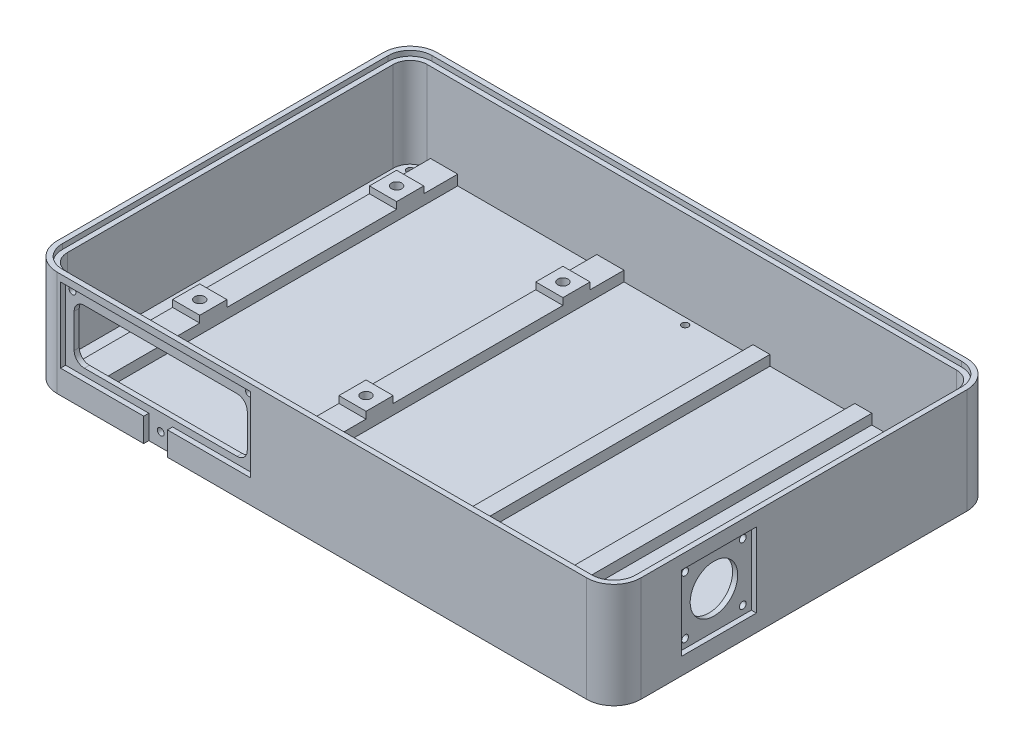
SolidWorks part; units mm, degrees
ref_plane "Спереди" through (0, 0, 0) normal (0, 0, 1) x (1, 0, 0)
ref_plane "Сверху" through (0, 0, 0) normal (0, 1, 0) x (1, 0, 0)
ref_plane "Справа" through (0, 0, 0) normal (1, 0, 0) x (0, 0, -1)
sketch "Эскиз1" plane through (0, 0, 0) normal (0, 1, 0) x (1, 0, 0)
  line L1 (8, 0) -> (164, 0)
  line L2 (0, 8) -> (0, 104)
  line L3 (8, 112) -> (164, 112)
  line L4 (172, 8) -> (172, 104)
  line L5 (8, 109) -> (164, 109)
  line L6 (3, 104) -> (3, 8)
  line L7 (8, 3) -> (164, 3)
  line L8 (169, 104) -> (169, 8)
  arc A0 (164, 0) -> (172, 8) centre (164, 8) ccw
  arc A2 (164, 109) -> (169, 104) centre (164, 104) cw
  arc A3 (172, 104) -> (164, 112) centre (164, 104) ccw
  arc A4 (8, 0) -> (0, 8) centre (8, 8) cw
  arc A5 (3, 8) -> (8, 3) centre (8, 8) ccw
  arc A6 (8, 109) -> (3, 104) centre (8, 104) ccw
  arc A7 (8, 112) -> (0, 104) centre (8, 104) ccw
  arc A8 (164, 3) -> (169, 8) centre (164, 8) ccw
  point P15 (169, 109)
  point P18 (172, 112)
  point P21 (0, 0)
  point P24 (3, 3)
  point P27 (3, 109)
  point P30 (0, 112)
  dimension "D7" = 8
  dimension "D8" = 5
  dimension "D9" = 5
  dimension "D10" = 5
  dimension "D11" = 5
  dimension "D1" = 172
  dimension "D2" = 112
  dimension "D3" = 166
  dimension "D4" = 106
  dimension "D5" = 3
  dimension "D6" = 3
extrude "Бобышка-Вытянуть1" add sketch "Эскиз1" along normal blind 28
sketch "Эскиз3" plane through (0, 0, 0) normal (0, 1, 0) x (1, 0, 0)
  line L0 (164, 109) -> (8, 109) construction
  line L1 (9, 109) -> (17, 109)
  line L2 (9, 109) -> (9, 3)
  line L3 (9, 3) -> (17, 3)
  line L4 (17, 109) -> (17, 3)
  line L6 (8, 3) -> (164, 3) construction
  line L9 (0, 104) -> (0, 8) construction
  line L12 (58, 109) -> (66, 109)
  line L13 (58, 109) -> (58, 3)
  line L14 (58, 3) -> (66, 3)
  line L15 (66, 109) -> (66, 3)
  dimension "D1" = 0
  dimension "D2" = 0
  dimension "D3" = 0
  dimension "D4" = 0
  dimension "D5" = 49
  dimension "D6" = 49
  dimension "D7" = 9
extrude "Бобышка-Вытянуть2" add sketch "Эскиз3" along normal blind 3 separate body
sketch "Эскиз6" plane through (0, 0, 0) normal (0, 1, 0) x (1, 0, 0)
  line L0 (0, 8) -> (0, 104)
  line L1 (8, 112) -> (164, 112)
  line L2 (164, 0) -> (8, 0)
  line L3 (172, 8) -> (172, 104)
  arc A0 (172, 8) -> (164, 0) centre (164, 8) cw
  arc A1 (172, 104) -> (164, 112) centre (164, 104) ccw
  arc A2 (8, 112) -> (0, 104) centre (8, 104) ccw
  arc A3 (0, 8) -> (8, 0) centre (8, 8) ccw
  point P13 (0, 0)
  dimension "D1" = 8
  dimension "D2" = 112
  dimension "D3" = 172
extrude "Бобышка-Вытянуть3" add sketch "Эскиз6" against normal blind 3
hole_wizard "Цековка для  болта с шестигранной головкой M51" positions "Эскиз15" profile "Эскиз14" counterbore size "M5" standard "Ansi Metric" end condition up to next
sketch "Эскиз15" plane through (0, -3, 0) normal (0, -1, 0) x (-1, 0, 0)
  line L0 (-164, 112) -> (-8, 112) construction
  line L1 (-172, 8) -> (-172, 104) construction
  line L2 (-8, 0) -> (-164, 0) construction
  line L3 (0, 104) -> (0, 8) construction
  line L4 (-164, 112) -> (-8, 112) construction
  line L5 (0, 104) -> (0, 8) construction
  line L6 (-8, 0) -> (-164, 0) construction
  point P0 (-6, 6)
  point P2 (-6, 106)
  point P4 (-166, 106)
  point P6 (-166, 6)
  point P18 (-86, 5)
  point P20 (-86, 107)
  dimension "D1" = 6
  dimension "D2" = 6
  dimension "D3" = 6
  dimension "D4" = 6
  dimension "D5" = 6
  dimension "D6" = 6
  dimension "D7" = 6
  dimension "D8" = 6
  dimension "D9" = 5
  dimension "D10" = 86
  dimension "D11" = 5
  dimension "D12" = 86
sketch "Эскиз14" plane through (6, -3, -6) normal (1, 0, 0) x (0, 0, -1)
  line L0 (0, 0) -> (0, 3)
  line L1 (0, 3) -> (1, 3)
  line L3 (1, 3) -> (1, 1)
  line L4 (1, 1) -> (1.5, 1)
  line L5 (1.5, 1) -> (1.5, 0)
  line L7 (1.5, 0) -> (0, 0)
  line L11 (0, -6.35) -> (0, 107.95) construction
  dimension "Диаметр сквозного отверстия" = 2
  dimension "Глубина сквозного отверстия" = 3
  dimension "Диаметр цековки" = 3
  dimension "Глубина цековки" = 1
sketch "Эскиз17" plane through (0, 0, 0) normal (0, 0, 1) x (1, 0, 0)
  line L0 (8, 28) -> (8, -3) construction
  line L1 (9, 26) -> (65, 26)
  line L2 (9, 26) -> (9, 4)
  line L3 (9, 4) -> (65, 4)
  line L4 (65, 26) -> (65, 4)
  line L6 (8, -3) -> (164, -3) construction
  line L7 (33.5, 4) -> (33.5, -3)
  line L8 (33.5, -3) -> (40.5, -3)
  line L9 (40.5, -3) -> (40.5, 4)
  line L10 (40.5, 4) -> (33.5, 4)
  line L11 (8, -3) -> (164, -3) construction
  point P8 (37, 4)
  point P9 (37, 26)
  point P10 (38.1, -3)
  line M5 (8, -3) -> (164, -3)
  dimension "D1" = 1
  dimension "D2" = 7
  dimension "D3" = 22
  dimension "D4" = 56
  dimension "D5" = 3.5
  dimension "D6" = 3.5
extrude "Вырез-Вытянуть2" cut sketch "Эскиз17" against normal blind 1.5 contours L4 L1 L2 L3 | L9 L3 L7 M5
sketch "Эскиз18" plane through (0, 0, -1.5) normal (0, 0, 1) x (1, 0, 0)
  line L0 (9, 4) -> (33.5, 4) construction
  line L1 (11.5, 22) -> (62.5, 22)
  line L2 (11.5, 22) -> (11.5, 6)
  line L3 (11.5, 6) -> (62.5, 6)
  line L4 (62.5, 22) -> (62.5, 6)
  line L5 (9, 26) -> (9, 4) construction
  line L6 (65, 26) -> (65, 4) construction
  dimension "D1" = 2
  dimension "D2" = 2.5
  dimension "D3" = 2.5
  dimension "D4" = 16
  dimension "D5" = 51
extrude "Вырез-Вытянуть3" cut sketch "Эскиз18" against normal up to next
sketch "Эскиз19" plane through (0, 3, 0) normal (0, 1, 0) x (1, 0, 0)
  line L0 (9, 109) -> (9, 3) construction
  line L1 (9, 99) -> (17, 99)
  line L2 (9, 99) -> (9, 91)
  line L3 (9, 91) -> (17, 91)
  line L4 (17, 99) -> (17, 91)
  line L5 (17, 3) -> (17, 109) construction
  line L6 (164, 109) -> (8, 109) construction
  line L7 (58, 109) -> (58, 3) construction
  line L8 (58, 99) -> (66, 99)
  line L9 (58, 99) -> (58, 91)
  line L10 (58, 91) -> (66, 91)
  line L11 (66, 99) -> (66, 91)
  line L12 (66, 3) -> (66, 109) construction
  line L13 (9, 109) -> (9, 3) construction
  line L14 (9, 41) -> (17, 41)
  line L15 (9, 41) -> (9, 33)
  line L16 (9, 33) -> (17, 33)
  line L17 (17, 41) -> (17, 33)
  line L18 (58, 109) -> (58, 3) construction
  line L19 (58, 41) -> (66, 41)
  line L20 (58, 41) -> (58, 33)
  line L21 (58, 33) -> (66, 33)
  line L22 (66, 41) -> (66, 33)
  line L23 (66, 3) -> (66, 109) construction
  point P18 (17, 95)
  point P19 (66, 95)
  point P34 (17, 37)
  point P35 (66, 37)
  dimension "D1" = 8
  dimension "D2" = 10
  dimension "D3" = 58
  dimension "D4" = 58
  dimension "D5" = 8
  dimension "D6" = 8
extrude "Бобышка-Вытянуть4" add sketch "Эскиз19" along normal blind 2
hole_wizard "Диаметр отверстия Ø3.0 (3)1" positions "Эскиз23" profile "Эскиз20" hole size "Ø3.0" standard "Ansi Metric"
sketch "Эскиз23" plane through (0, 5, 0) normal (0, 1, 0) x (1, 0, 0)
  line L0 (13, 99) -> (13, 91) construction
  line L1 (17, 99) -> (9, 99) construction
  line L2 (9, 91) -> (17, 91) construction
  line L4 (9, 99) -> (9, 91) construction
  line L5 (9, 95) -> (17, 95) construction
  line L6 (17, 91) -> (17, 99) construction
  line L7 (66, 95) -> (62, 99) construction
  line L8 (66, 3) -> (66, 109) construction
  line L9 (66, 99) -> (58, 99) construction
  line L10 (62, 99) -> (62, 91) construction
  line L11 (58, 91) -> (66, 91) construction
  line L12 (62, 33) -> (62, 41) construction
  line L13 (58, 33) -> (66, 33) construction
  line L14 (66, 41) -> (58, 41) construction
  line L15 (62, 41) -> (62, 37) construction
  line L16 (62, 37) -> (9, 37) construction
  line L17 (9, 41) -> (9, 33) construction
  line L18 (9, 37) -> (17, 37) construction
  line L19 (17, 33) -> (17, 41) construction
  line L20 (17, 37) -> (13, 37) construction
  line L21 (13, 37) -> (13, 33) construction
  line L22 (9, 33) -> (17, 33) construction
  point P17 (13, 95)
  point P34 (62, 95)
  point P44 (62, 37)
  point P54 (13, 37)
sketch "Эскиз20" plane through (13, 5, -95) normal (1, 0, 0) x (0, 0, 1)
  line L0 (0, 0) -> (0, 5.9013)
  line L1 (0, 5.9013) -> (1.5, 5)
  line L2 (1.5, 5) -> (1.5, 0)
  line L5 (1.5, 0) -> (0, 0)
  line L10 (0, 5.9013) -> (-1.5, 5) construction
  line L11 (0, -6.35) -> (0, 107.95) construction
  dimension "Диаметр отверстия" = 3
  dimension "Глубина отверстия" = 5
  dimension "Угол заточки сверла" = 118
hole_wizard "Диаметр отверстия Ø2.0 (2)1" positions "Эскиз26" profile "Эскиз25" hole size "Ø2.0" standard "Ansi Metric"
sketch "Эскиз26" plane through (0, 0, -1.5) normal (0, 0, 1) x (1, 0, 0)
  line L0 (33.5, 4) -> (33.5, -3) construction
  line L1 (33.5, -3) -> (40.5, -3) construction
  line L2 (9, 26) -> (65, 26) construction
  line L3 (9, 26) -> (9, 4) construction
  line L4 (65, 26) -> (65, 4) construction
  point P0 (37, 1)
  point P3 (33.5, 0.5)
  point P8 (11, 24)
  point P15 (63, 24)
  dimension "D1" = 3.5
  dimension "D2" = 4
  dimension "D3" = 2
  dimension "D4" = 2
  dimension "D5" = 2
sketch "Эскиз25" plane through (37, 1, -1.5) normal (1, 0, 0) x (0, -1, 0)
  line L0 (0, 0) -> (0, 5.6009)
  line L1 (0, 5.6009) -> (1, 5)
  line L2 (1, 5) -> (1, 0)
  line L5 (1, 0) -> (0, 0)
  line L10 (0, 5.6009) -> (-1, 5) construction
  line L11 (0, -6.35) -> (0, 107.95) construction
  dimension "Диаметр отверстия" = 2
  dimension "Глубина отверстия" = 5
  dimension "Угол заточки сверла" = 118
sketch "Эскиз27" plane through (0, 28, 0) normal (0, 1, 0) x (1, 0, 0)
  line L8 (170.5, 8) -> (170.5, 104)
  line L9 (164, 110.5) -> (8, 110.5)
  line L10 (1.5, 104) -> (1.5, 8)
  line L11 (8, 1.5) -> (164, 1.5)
  line L12 (170.5, 8) -> (170.5, 104)
  line L13 (164, 110.5) -> (8, 110.5)
  line L14 (1.5, 104) -> (1.5, 8)
  line L15 (8, 1.5) -> (164, 1.5)
  arc A8 (164, 1.5) -> (170.5, 8) centre (164, 8) ccw
  arc A9 (170.5, 104) -> (164, 110.5) centre (164, 104) ccw
  arc A10 (8, 110.5) -> (1.5, 104) centre (8, 104) ccw
  arc A11 (1.5, 8) -> (8, 1.5) centre (8, 8) ccw
  arc A12 (164, 1.5) -> (170.5, 8) centre (164, 8) ccw
  arc A13 (170.5, 104) -> (164, 110.5) centre (164, 104) ccw
  arc A14 (8, 110.5) -> (1.5, 104) centre (8, 104) ccw
  arc A15 (1.5, 8) -> (8, 1.5) centre (8, 8) ccw
  dimension "D1" = 1.5
extrude "Вырез-Вытянуть4" cut sketch "Эскиз27" against normal blind 1.5
fillet "Скругление1" radius 3 4 edges at (62.5, 6, -2.25) (62.5, 22, -2.25) (11.5, 6, -2.25) (11.5, 22, -2.25)
sketch "Эскиз28" plane through (0, 0, 0) normal (0, 1, 0) x (1, 0, 0)
  line L0 (164, 109) -> (66, 109) construction
  line L1 (104, 109) -> (109, 109)
  line L2 (104, 109) -> (104, 3)
  line L3 (104, 3) -> (109, 3)
  line L4 (109, 109) -> (109, 3)
  line L5 (66, 3) -> (164, 3) construction
  line L6 (8, 3) -> (164, 3) construction
  line L7 (134, 109) -> (139, 109)
  line L8 (134, 109) -> (134, 3)
  line L9 (134, 3) -> (139, 3)
  line L10 (139, 109) -> (139, 3)
  line L11 (169, 8) -> (169, 104) construction
  dimension "D1" = 30
  dimension "D2" = 30
  dimension "D3" = 30
  dimension "D4" = 5
extrude "Бобышка-Вытянуть5" add sketch "Эскиз28" along normal blind 3
sketch "Эскиз29" plane through (172, 0, 0) normal (1, 0, 0) x (0, 0, -1)
  line L0 (8, 28) -> (8, -3) construction
  line L1 (20, 24) -> (42, 24)
  line L2 (20, 24) -> (20, 2)
  line L3 (20, 2) -> (42, 2)
  line L4 (42, 24) -> (42, 2)
  line L5 (8, 28) -> (104, 28) construction
  dimension "D1" = 22
  dimension "D2" = 22
  dimension "D3" = 12
  dimension "D4" = 4
extrude "Вырез-Вытянуть5" cut sketch "Эскиз29" against normal blind 1.5
sketch "Эскиз30" plane through (170.5, 0, 0) normal (1, 0, 0) x (0, 0, -1)
  line L0 (42, 24) -> (20, 24) construction
  line L1 (20, 24) -> (20, 2) construction
  circle A0 centre (31, 13) radius 7
  dimension "D1" = 11
  dimension "D2" = 11
extrude "Вырез-Вытянуть6" cut sketch "Эскиз30" against normal blind 1.5
hole_wizard "Диаметр отверстия Ø2.0 (2)2" positions "Эскиз32" profile "Эскиз33" hole size "Ø2.0" standard "Ansi Metric"
sketch "Эскиз32" plane through (170.5, 0, 0) normal (1, 0, 0) x (0, 0, -1)
  line L0 (20, 24) -> (20, 2) construction
  line L3 (42, 24) -> (20, 24) construction
  line L4 (42, 2) -> (42, 24) construction
  line L5 (20, 2) -> (42, 2) construction
  line L6 (20, 2) -> (42, 2) construction
  point P0 (22.5, 21.5)
  point P2 (39.5, 21.5)
  point P4 (39.5, 4.5)
  point P6 (22.5, 4.5)
  point P15 (22.2314, 24)
  dimension "D1" = 2.5
  dimension "D2" = 2.5
  dimension "D3" = 2.5
  dimension "D4" = 2.5
  dimension "D5" = 2.5
  dimension "D6" = 2.5
  dimension "D7" = 2.5
  dimension "D8" = 2.5
sketch "Эскиз33" plane through (170.5, 21.5, -22.5) normal (0, 1, 0) x (0, 0, -1)
  line L0 (0, 0) -> (0, 2.1009)
  line L1 (0, 2.1009) -> (1, 1.5)
  line L2 (1, 1.5) -> (1, 0)
  line L5 (1, 0) -> (0, 0)
  line L10 (0, 2.1009) -> (-1, 1.5) construction
  line L11 (0, -6.35) -> (0, 107.95) construction
  dimension "Диаметр отверстия" = 2
  dimension "Глубина отверстия" = 1.5
  dimension "Угол заточки сверла" = 118
